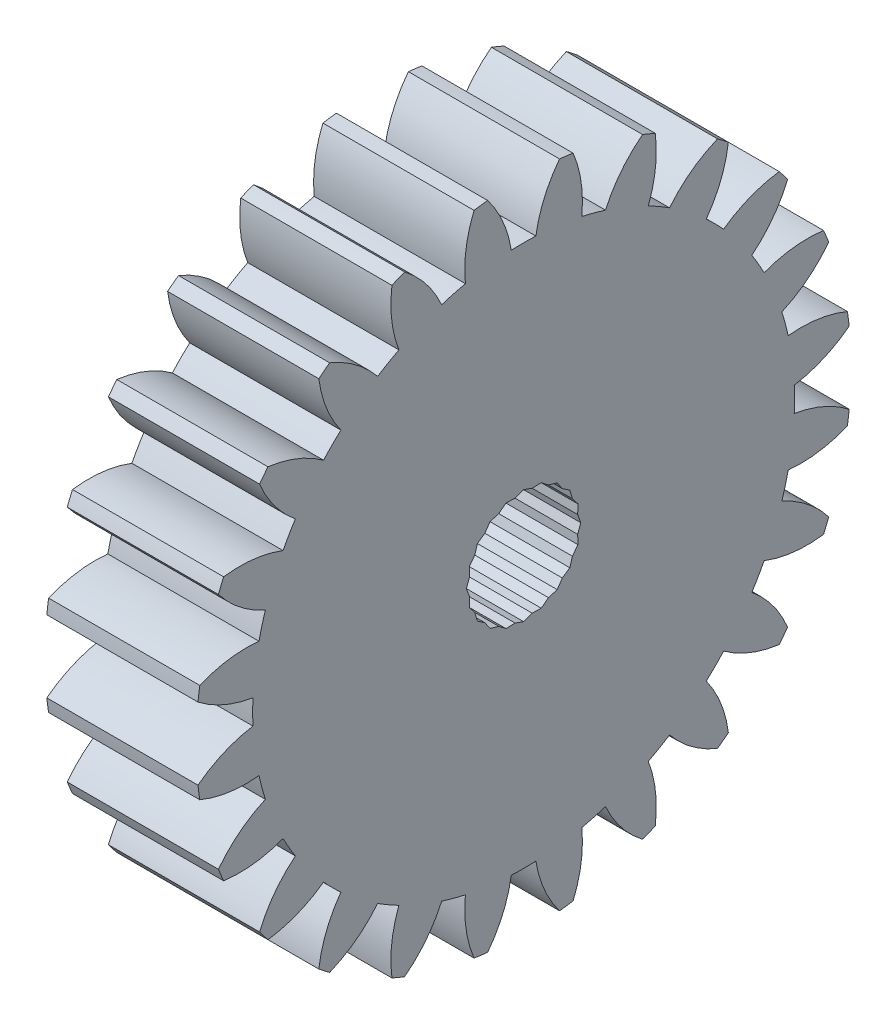
SolidWorks part; units mm, degrees
ref_plane "Front Plane" through (0, 0, 0) normal (0, 0, 1) x (1, 0, 0)
ref_plane "Top Plane" through (0, 0, 0) normal (0, 1, 0) x (1, 0, 0)
ref_plane "Right Plane" through (0, 0, 0) normal (1, 0, 0) x (0, 0, -1)
sketch "Sketch1" plane through (0, 0, 0) normal (0, 0, 1) x (1, 0, 0)
  line L0 (-10, 0) -> (60, 0) construction
  line L1 (0, 0) -> (0, 13.7583)
  line L2 (0, 0) -> (6.35, 0)
  line L3 (6.35, 0) -> (6.35, 13.7583)
  line L4 (6.35, 13.7583) -> (0, 13.7583)
  point P1 (0, 0)
  dimension "Diameter" = 27.5167
  dimension "Thickness" = 6.35
revolve "Revolve1" add sketch "Sketch1" angle 360 about L0
sketch "Sketch2" plane through (0, 0, 0) normal (-1, 0, 0) x (0, 0, 1)
  line L1 (0, 0) -> (0, 61.9835) construction
  line L2 (0, 0) -> (-0.9053, 12.6677) construction
  line L3 (0, 0) -> (-3.3095, 25.138) construction
  line L4 (-0.9053, 12.6677) -> (-1.6547, 12.569) construction
  arc A0 (0.516, 11.3675) -> (-0.516, 11.3675) centre (0, 0) ccw
  arc A1 (1.5285, 13.6987) -> (-1.5285, 13.6987) centre (0, 0) ccw
  circle A2 centre (0, 0) radius 12.7 construction
  circle A3 centre (0, 0) radius 11.9341 construction
  arc A4 (-0.516, 11.3675) -> (-1.5285, 13.6987) centre (-5.5336, 10.5736) ccw
  arc A5 (1.5285, 13.6987) -> (0.516, 11.3675) centre (5.5336, 10.5736) ccw
  arc A6 (2.4437, 11.1137) -> (2.069, 13.6276) centre (-2.6084, 11.6456) ccw
  arc A7 (5.022, 12.8363) -> (2.069, 13.6276) centre (0, 0) ccw
  arc A8 (5.022, 12.8363) -> (3.4405, 10.8466) centre (8.0817, 8.7812) ccw
  arc A9 (3.4405, 10.8466) -> (2.4437, 11.1137) centre (0, 0) ccw
  arc A10 (5.2369, 10.1025) -> (5.5256, 12.6277) centre (0.4946, 11.9238) ccw
  arc A11 (8.1731, 11.0992) -> (5.5256, 12.6277) centre (0, 0) ccw
  arc A12 (8.1731, 11.0992) -> (6.1306, 9.5865) centre (10.0791, 6.3903) ccw
  arc A13 (6.1306, 9.5865) -> (5.2369, 10.1025) centre (0, 0) ccw
  arc A14 (7.6732, 8.4029) -> (8.6056, 10.7673) centre (3.5639, 11.3895) ccw
  arc A15 (10.7673, 8.6056) -> (8.6056, 10.7673) centre (0, 0) ccw
  arc A16 (10.7673, 8.6056) -> (8.4029, 7.6732) centre (11.3895, 3.5639) ccw
  arc A17 (8.4029, 7.6732) -> (7.6732, 8.4029) centre (0, 0) ccw
  arc A18 (9.5865, 6.1306) -> (11.0992, 8.1731) centre (6.3903, 10.0791) ccw
  arc A19 (12.6277, 5.5256) -> (11.0992, 8.1731) centre (0, 0) ccw
  arc A20 (12.6277, 5.5256) -> (10.1025, 5.2369) centre (11.9238, 0.4946) ccw
  arc A21 (10.1025, 5.2369) -> (9.5865, 6.1306) centre (0, 0) ccw
  arc A22 (10.8466, 3.4405) -> (12.8363, 5.022) centre (8.7812, 8.0817) ccw
  arc A23 (13.6276, 2.069) -> (12.8363, 5.022) centre (0, 0) ccw
  arc A24 (13.6276, 2.069) -> (11.1137, 2.4437) centre (11.6456, -2.6084) ccw
  arc A25 (11.1137, 2.4437) -> (10.8466, 3.4405) centre (0, 0) ccw
  arc A26 (11.3675, 0.516) -> (13.6987, 1.5285) centre (10.5736, 5.5336) ccw
  arc A27 (13.6987, -1.5285) -> (13.6987, 1.5285) centre (0, 0) ccw
  arc A28 (13.6987, -1.5285) -> (11.3675, -0.516) centre (10.5736, -5.5336) ccw
  arc A29 (11.3675, -0.516) -> (11.3675, 0.516) centre (0, 0) ccw
  arc A30 (11.1137, -2.4437) -> (13.6276, -2.069) centre (11.6456, 2.6084) ccw
  arc A31 (12.8363, -5.022) -> (13.6276, -2.069) centre (0, 0) ccw
  arc A32 (12.8363, -5.022) -> (10.8466, -3.4405) centre (8.7812, -8.0817) ccw
  arc A33 (10.8466, -3.4405) -> (11.1137, -2.4437) centre (0, 0) ccw
  arc A34 (10.1025, -5.2369) -> (12.6277, -5.5256) centre (11.9238, -0.4946) ccw
  arc A35 (11.0992, -8.1731) -> (12.6277, -5.5256) centre (0, 0) ccw
  arc A36 (11.0992, -8.1731) -> (9.5865, -6.1306) centre (6.3903, -10.0791) ccw
  arc A37 (9.5865, -6.1306) -> (10.1025, -5.2369) centre (0, 0) ccw
  arc A38 (8.4029, -7.6732) -> (10.7673, -8.6056) centre (11.3895, -3.5639) ccw
  arc A39 (8.6056, -10.7673) -> (10.7673, -8.6056) centre (0, 0) ccw
  arc A40 (8.6056, -10.7673) -> (7.6732, -8.4029) centre (3.5639, -11.3895) ccw
  arc A41 (7.6732, -8.4029) -> (8.4029, -7.6732) centre (0, 0) ccw
  arc A42 (6.1306, -9.5865) -> (8.1731, -11.0992) centre (10.0791, -6.3903) ccw
  arc A43 (5.5256, -12.6277) -> (8.1731, -11.0992) centre (0, 0) ccw
  arc A44 (5.5256, -12.6277) -> (5.2369, -10.1025) centre (0.4946, -11.9238) ccw
  arc A45 (5.2369, -10.1025) -> (6.1306, -9.5865) centre (0, 0) ccw
  arc A46 (3.4405, -10.8466) -> (5.022, -12.8363) centre (8.0817, -8.7812) ccw
  arc A47 (2.069, -13.6276) -> (5.022, -12.8363) centre (0, 0) ccw
  arc A48 (2.069, -13.6276) -> (2.4437, -11.1137) centre (-2.6084, -11.6456) ccw
  arc A49 (2.4437, -11.1137) -> (3.4405, -10.8466) centre (0, 0) ccw
  arc A50 (0.516, -11.3675) -> (1.5285, -13.6987) centre (5.5336, -10.5736) ccw
  arc A51 (-1.5285, -13.6987) -> (1.5285, -13.6987) centre (0, 0) ccw
  arc A52 (-1.5285, -13.6987) -> (-0.516, -11.3675) centre (-5.5336, -10.5736) ccw
  arc A53 (-0.516, -11.3675) -> (0.516, -11.3675) centre (0, 0) ccw
  arc A54 (-2.4437, -11.1137) -> (-2.069, -13.6276) centre (2.6084, -11.6456) ccw
  arc A55 (-5.022, -12.8363) -> (-2.069, -13.6276) centre (0, 0) ccw
  arc A56 (-5.022, -12.8363) -> (-3.4405, -10.8466) centre (-8.0817, -8.7812) ccw
  arc A57 (-3.4405, -10.8466) -> (-2.4437, -11.1137) centre (0, 0) ccw
  arc A58 (-5.2369, -10.1025) -> (-5.5256, -12.6277) centre (-0.4946, -11.9238) ccw
  arc A59 (-8.1731, -11.0992) -> (-5.5256, -12.6277) centre (0, 0) ccw
  arc A60 (-8.1731, -11.0992) -> (-6.1306, -9.5865) centre (-10.0791, -6.3903) ccw
  arc A61 (-6.1306, -9.5865) -> (-5.2369, -10.1025) centre (0, 0) ccw
  arc A62 (-7.6732, -8.4029) -> (-8.6056, -10.7673) centre (-3.5639, -11.3895) ccw
  arc A63 (-10.7673, -8.6056) -> (-8.6056, -10.7673) centre (0, 0) ccw
  arc A64 (-10.7673, -8.6056) -> (-8.4029, -7.6732) centre (-11.3895, -3.5639) ccw
  arc A65 (-8.4029, -7.6732) -> (-7.6732, -8.4029) centre (0, 0) ccw
  arc A66 (-9.5865, -6.1306) -> (-11.0992, -8.1731) centre (-6.3903, -10.0791) ccw
  arc A67 (-12.6277, -5.5256) -> (-11.0992, -8.1731) centre (0, 0) ccw
  arc A68 (-12.6277, -5.5256) -> (-10.1025, -5.2369) centre (-11.9238, -0.4946) ccw
  arc A69 (-10.1025, -5.2369) -> (-9.5865, -6.1306) centre (0, 0) ccw
  arc A70 (-10.8466, -3.4405) -> (-12.8363, -5.022) centre (-8.7812, -8.0817) ccw
  arc A71 (-13.6276, -2.069) -> (-12.8363, -5.022) centre (0, 0) ccw
  arc A72 (-13.6276, -2.069) -> (-11.1137, -2.4437) centre (-11.6456, 2.6084) ccw
  arc A73 (-11.1137, -2.4437) -> (-10.8466, -3.4405) centre (0, 0) ccw
  arc A74 (-11.3675, -0.516) -> (-13.6987, -1.5285) centre (-10.5736, -5.5336) ccw
  arc A75 (-13.6987, 1.5285) -> (-13.6987, -1.5285) centre (0, 0) ccw
  arc A76 (-13.6987, 1.5285) -> (-11.3675, 0.516) centre (-10.5736, 5.5336) ccw
  arc A77 (-11.3675, 0.516) -> (-11.3675, -0.516) centre (0, 0) ccw
  arc A78 (-11.1137, 2.4437) -> (-13.6276, 2.069) centre (-11.6456, -2.6084) ccw
  arc A79 (-12.8363, 5.022) -> (-13.6276, 2.069) centre (0, 0) ccw
  arc A80 (-12.8363, 5.022) -> (-10.8466, 3.4405) centre (-8.7812, 8.0817) ccw
  arc A81 (-10.8466, 3.4405) -> (-11.1137, 2.4437) centre (0, 0) ccw
  arc A82 (-10.1025, 5.2369) -> (-12.6277, 5.5256) centre (-11.9238, 0.4946) ccw
  arc A83 (-11.0992, 8.1731) -> (-12.6277, 5.5256) centre (0, 0) ccw
  arc A84 (-11.0992, 8.1731) -> (-9.5865, 6.1306) centre (-6.3903, 10.0791) ccw
  arc A85 (-9.5865, 6.1306) -> (-10.1025, 5.2369) centre (0, 0) ccw
  arc A86 (-8.4029, 7.6732) -> (-10.7673, 8.6056) centre (-11.3895, 3.5639) ccw
  arc A87 (-8.6056, 10.7673) -> (-10.7673, 8.6056) centre (0, 0) ccw
  arc A88 (-8.6056, 10.7673) -> (-7.6732, 8.4029) centre (-3.5639, 11.3895) ccw
  arc A89 (-7.6732, 8.4029) -> (-8.4029, 7.6732) centre (0, 0) ccw
  arc A90 (-6.1306, 9.5865) -> (-8.1731, 11.0992) centre (-10.0791, 6.3903) ccw
  arc A91 (-5.5256, 12.6277) -> (-8.1731, 11.0992) centre (0, 0) ccw
  arc A92 (-5.5256, 12.6277) -> (-5.2369, 10.1025) centre (-0.4946, 11.9238) ccw
  arc A93 (-5.2369, 10.1025) -> (-6.1306, 9.5865) centre (0, 0) ccw
  arc A94 (-3.4405, 10.8466) -> (-5.022, 12.8363) centre (-8.0817, 8.7812) ccw
  arc A95 (-2.069, 13.6276) -> (-5.022, 12.8363) centre (0, 0) ccw
  arc A96 (-2.069, 13.6276) -> (-2.4437, 11.1137) centre (2.6084, 11.6456) ccw
  arc A97 (-2.4437, 11.1137) -> (-3.4405, 10.8466) centre (0, 0) ccw
  point P156 (0, 0)
  dimension "Root_dia" = 22.7584
  dimension "Overcut_dia" = 27.5675
  dimension "Pitch_dia" = 25.4
  dimension "Base_dia" = 23.8682
  dimension "Flank_rad" = 5.08
  dimension "Half_ang" = 7.5
  dimension "Half_CT" = 0.7559
extrude "Cut-Extrude1" cut sketch "Sketch2" against normal through all
sketch "Sketch3" plane through (0, 0, 0) normal (-1, 0, 0) x (0, 0, 1)
  line L0 (0, 2.4) -> (0, -2.4) construction
  line L1 (0.3754, 2.3705) -> (-0.3754, -2.3705) construction
  line L2 (0.7416, 2.2825) -> (-0.7416, -2.2825) construction
  line L3 (1.0896, 2.1384) -> (-1.0896, -2.1384) construction
  line L4 (1.4107, 1.9416) -> (-1.4107, -1.9416) construction
  line L5 (1.6971, 1.6971) -> (-1.6971, -1.6971) construction
  line L6 (1.9416, 1.4107) -> (-1.9416, -1.4107) construction
  line L7 (2.1384, 1.0896) -> (-2.1384, -1.0896) construction
  line L8 (2.2825, 0.7416) -> (-2.2825, -0.7416) construction
  line L9 (2.3705, 0.3754) -> (-2.3705, -0.3754) construction
  line L10 (2.4, 0) -> (-2.4, 0) construction
  line L11 (2.3705, -0.3754) -> (-2.3705, 0.3754) construction
  line L12 (2.2825, -0.7416) -> (-2.2825, 0.7416) construction
  line L13 (2.1384, -1.0896) -> (-2.1384, 1.0896) construction
  line L14 (1.9416, -1.4107) -> (-1.9416, 1.4107) construction
  line L15 (1.6971, -1.6971) -> (-1.6971, 1.6971) construction
  line L16 (1.4107, -1.9416) -> (-1.4107, 1.9416) construction
  line L17 (1.0896, -2.1384) -> (-1.0896, 2.1384) construction
  line L18 (0.7416, -2.2825) -> (-0.7416, 2.2825) construction
  line L19 (0.3754, -2.3705) -> (-0.3754, 2.3705) construction
  line L20 (0, -2.4) -> (0, 2.4) construction
  line L21 (-0.3754, -2.3705) -> (0.3754, 2.3705) construction
  line L22 (-0.7416, -2.2825) -> (0.7416, 2.2825) construction
  line L23 (-1.0896, -2.1384) -> (1.0896, 2.1384) construction
  line L24 (-1.4107, -1.9416) -> (1.4107, 1.9416) construction
  line L25 (-1.6971, -1.6971) -> (1.6971, 1.6971) construction
  line L26 (-1.9416, -1.4107) -> (1.9416, 1.4107) construction
  line L27 (-2.1384, -1.0896) -> (2.1384, 1.0896) construction
  line L28 (-2.2825, -0.7416) -> (2.2825, 0.7416) construction
  line L29 (-2.3705, -0.3754) -> (2.3705, 0.3754) construction
  line L30 (-2.4, 0) -> (2.4, 0) construction
  line L31 (-2.3705, 0.3754) -> (2.3705, -0.3754) construction
  line L32 (-2.2825, 0.7416) -> (2.2825, -0.7416) construction
  line L33 (-2.1384, 1.0896) -> (2.1384, -1.0896) construction
  line L34 (-1.9416, 1.4107) -> (1.9416, -1.4107) construction
  line L35 (-1.6971, 1.6971) -> (1.6971, -1.6971) construction
  line L36 (-1.4107, 1.9416) -> (1.4107, -1.9416) construction
  line L37 (-1.0896, 2.1384) -> (1.0896, -2.1384) construction
  line L38 (-0.7416, 2.2825) -> (0.7416, -2.2825) construction
  line L39 (-0.3754, 2.3705) -> (0.3754, -2.3705) construction
  line L40 (-0.3598, 2.2717) -> (0, 2.4)
  line L41 (0, 2.4) -> (0.3598, 2.2717)
  line L42 (0.3598, 2.2717) -> (0.7416, 2.2825)
  line L43 (0.7416, 2.2825) -> (1.0442, 2.0493)
  line L44 (1.0442, 2.0493) -> (1.4107, 1.9416)
  line L45 (1.4107, 1.9416) -> (1.6263, 1.6263)
  line L46 (1.6263, 1.6263) -> (1.9416, 1.4107)
  line L47 (1.9416, 1.4107) -> (2.0493, 1.0442)
  line L48 (2.0493, 1.0442) -> (2.2825, 0.7416)
  line L49 (2.2825, 0.7416) -> (2.2717, 0.3598)
  line L50 (2.2717, 0.3598) -> (2.4, 0)
  line L51 (2.4, 0) -> (2.2717, -0.3598)
  line L52 (2.2717, -0.3598) -> (2.2825, -0.7416)
  line L53 (2.2825, -0.7416) -> (2.0493, -1.0442)
  line L54 (2.0493, -1.0442) -> (1.9416, -1.4107)
  line L55 (1.9416, -1.4107) -> (1.6263, -1.6263)
  line L56 (1.6263, -1.6263) -> (1.4107, -1.9416)
  line L57 (1.4107, -1.9416) -> (1.0442, -2.0493)
  line L58 (1.0442, -2.0493) -> (0.7416, -2.2825)
  line L59 (0.7416, -2.2825) -> (0.3598, -2.2717)
  line L60 (0.3598, -2.2717) -> (0, -2.4)
  line L61 (0, -2.4) -> (-0.3598, -2.2717)
  line L62 (-0.3598, -2.2717) -> (-0.7416, -2.2825)
  line L63 (-0.7416, -2.2825) -> (-1.0442, -2.0493)
  line L64 (-1.0442, -2.0493) -> (-1.4107, -1.9416)
  line L65 (-1.4107, -1.9416) -> (-1.6263, -1.6263)
  line L66 (-1.6263, -1.6263) -> (-1.9416, -1.4107)
  line L67 (-1.9416, -1.4107) -> (-2.0493, -1.0442)
  line L68 (-2.0493, -1.0442) -> (-2.2825, -0.7416)
  line L69 (-2.2825, -0.7416) -> (-2.2717, -0.3598)
  line L70 (-2.2717, -0.3598) -> (-2.4, 0)
  line L71 (-2.4, 0) -> (-2.2717, 0.3598)
  line L72 (-2.2717, 0.3598) -> (-2.2825, 0.7416)
  line L73 (-2.2825, 0.7416) -> (-2.0493, 1.0442)
  line L74 (-2.0493, 1.0442) -> (-1.9416, 1.4107)
  line L75 (-1.9416, 1.4107) -> (-1.6263, 1.6263)
  line L76 (-1.6263, 1.6263) -> (-1.4107, 1.9416)
  line L77 (-1.4107, 1.9416) -> (-1.0442, 2.0493)
  line L78 (-1.0442, 2.0493) -> (-0.7416, 2.2825)
  line L79 (-0.7416, 2.2825) -> (-0.3598, 2.2717)
  circle A0 centre (0, 0) radius 2.3 construction
  circle A1 centre (0, 0) radius 2.4 construction
  point P2 (-5.1004, 2.2262)
  point P47 (0, 0)
  point P86 (0, 0)
  point P145 (0, 0)
  dimension "D1" = 4.8
  dimension "D2" = 4.6
extrude "Cut-Extrude2" cut sketch "Sketch3" against normal through all
